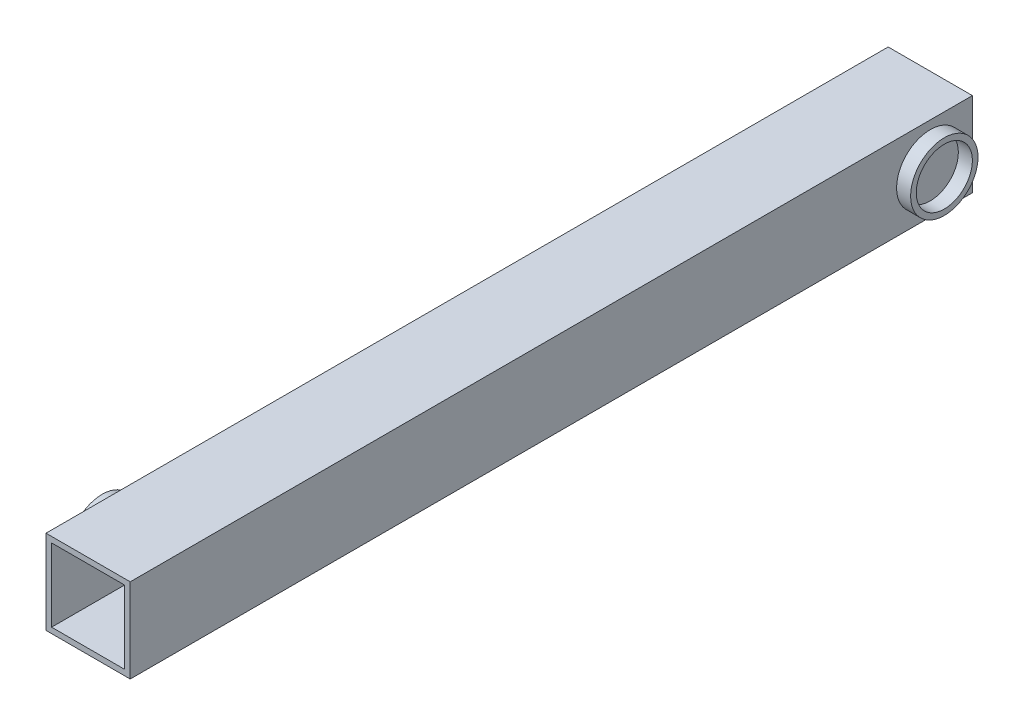
SolidWorks part; units mm, degrees
ref_plane "Front Plane" through (0, 0, 0) normal (0, 0, 1) x (1, 0, 0)
ref_plane "Top Plane" through (0, 0, 0) normal (0, 1, 0) x (1, 0, 0)
ref_plane "Right Plane" through (0, 0, 0) normal (1, 0, 0) x (0, 0, -1)
sketch "Sketch1" plane through (0, 0, 0) normal (0, 0, 1) x (1, 0, 0)
  line L0 (-13, 13) -> (-13, -13)
  line L1 (-15, 15) -> (15, 15)
  line L2 (-15, 15) -> (-15, -15)
  line L3 (-15, -15) -> (15, -15)
  line L4 (15, 15) -> (15, -15)
  line L5 (-15, 15) -> (15, -15) construction
  line L6 (-15, -15) -> (15, 15) construction
  line L7 (-13, -13) -> (13, -13)
  line L8 (13, 13) -> (13, -13)
  line L9 (-13, 13) -> (13, 13)
  point P0 (0, 0)
  dimension "D1" = 30
  dimension "D2" = 30
  dimension "D3" = 2
extrude "Boss-Extrude1" add sketch "Sketch1" along normal blind 300
sketch "Sketch2" plane through (15, 0, 0) normal (1, 0, 0) x (0, 0, -1)
  line L0 (-150, 15) -> (-150, -15) construction
  line L1 (-300, 15) -> (0, 15) construction
  line L2 (-300, -15) -> (0, -15) construction
  circle A0 centre (-15, 0) radius 12
  circle A1 centre (-15, 0) radius 10
  dimension "D1" = 24
  dimension "D3" = 15
  dimension "D2" = 2
extrude "Boss-Extrude2" add sketch "Sketch2" along normal blind 5
sketch "Sketch3" plane through (-15, 0, 0) normal (-1, 0, 0) x (0, 0, 1)
  circle A0 centre (275, 0) radius 10
  circle A3 centre (275, 0) radius 12
  dimension "D1" = 20
  dimension "D2" = 275
extrude "Boss-Extrude3" add sketch "Sketch3" along normal blind 5
